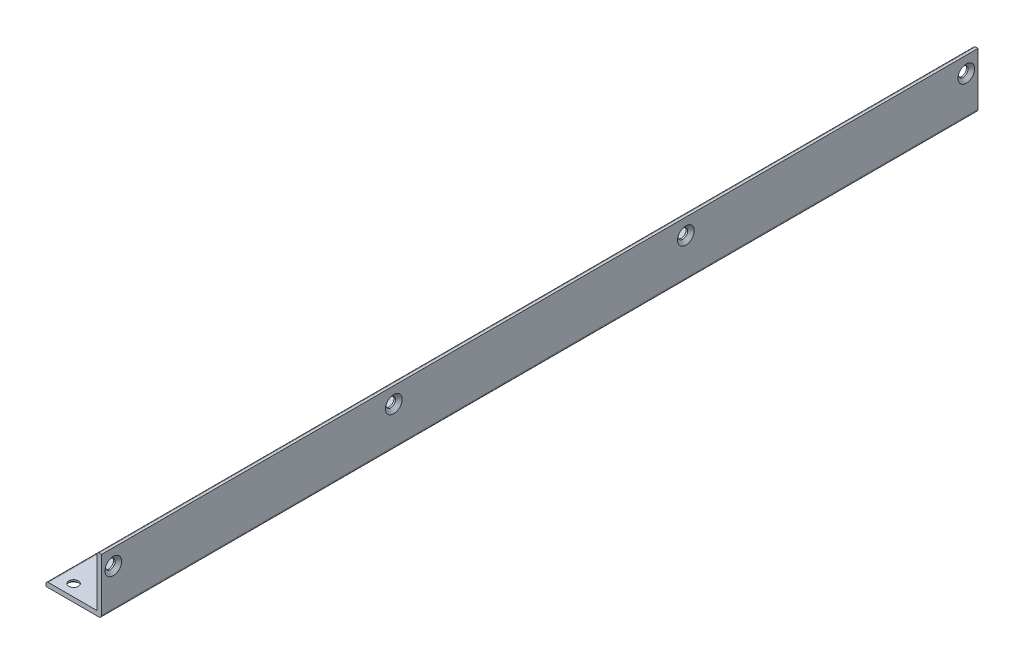
SolidWorks part; units mm, degrees
material "6061-T6 (SS)"
ref_plane "Front Plane" through (0, 0, 0) normal (0, 0, 1) x (1, 0, 0)
ref_plane "Top Plane" through (0, 0, 0) normal (0, 1, 0) x (1, 0, 0)
ref_plane "Right Plane" through (0, 0, 0) normal (1, 0, 0) x (0, 0, -1)
sketch "Sketch2" plane through (0, 0, 0) normal (0, 0, 1) x (1, 0, 0)
  line L0 (-9.525, 0) -> (9.525, 0)
  line L1 (9.525, 0) -> (9.525, 19.05)
  line L2 (9.525, 19.05) -> (7.9375, 19.05) construction
  line L3 (7.9375, 18.2563) -> (7.9375, 2.3812)
  line L4 (7.1438, 1.5875) -> (-8.7313, 1.5875)
  line L5 (-9.525, 0) -> (-9.525, 1.5875) construction
  line L6 (8.7313, 19.05) -> (9.525, 19.05)
  line L7 (-9.525, 0.7937) -> (-9.525, 0)
  arc A0 (7.9375, 18.2563) -> (8.7313, 19.05) centre (8.7313, 18.2563) cw
  arc A1 (-9.525, 0.7937) -> (-8.7313, 1.5875) centre (-8.7313, 0.7937) cw
  arc A2 (7.9375, 2.3812) -> (7.1438, 1.5875) centre (7.1438, 2.3812) cw
  dimension "Vert" = 19.05
  dimension "Horz" = 19.05
  dimension "Thickness" = 1.5875
extrude "Boss-Extrude1" add sketch "Sketch2" along normal mid plane 300
ref_plane "Contact Plane 1" through (0, 1.5875, 0) normal (0, 1, 0) x (1, 0, 0)
ref_plane "Contact Plane 2" through (7.9375, 0, 0) normal (-1, 0, 0) x (0, 0, 1)
sketch "Sketch6" plane through (0, 0, 0) normal (0, -1, 0) x (1, 0, 0)
  line L0 (9.525, 146) -> (-4.0625, 146) construction
  line L1 (9.525, 150) -> (9.525, -150) construction
  line L2 (-9.525, 150) -> (9.525, 150) construction
  line L3 (9.525, 0) -> (-9.525, 0) construction
  line L4 (-9.525, 150) -> (-9.525, -150) construction
  point P7 (-4.0625, 146)
  point P11 (-4.0625, -146)
  dimension "D1" = 4
  dimension "D2" = 13.5875
hole_wizard "CSK for #4 Flat Head Machine Screw (100)1" positions "Sketch7" profile "Sketch8" countersink size "#4" standard "ANSI Inch" end condition through all
sketch "Sketch7" plane through (0, 0, 0) normal (0, -1, 0) x (-1, 0, 0)
  point P0 (4.0625, -146)
  point P3 (4.0625, 146)
sketch "Sketch8" plane through (-4.0625, 0, 146) normal (1, 0, 0) x (0, 0, -1)
  line L0 (0, 0) -> (0, 19.05)
  line L1 (0, 19.05) -> (1.6319, 19.05)
  line L2 (1.6319, 19.05) -> (1.6319, 1.0284)
  line L3 (1.6319, 1.0284) -> (2.8575, 0)
  line L5 (2.8575, 0) -> (0, 0)
  line L6 (-1.6319, 1.0284) -> (-2.8575, 0) construction
  line L11 (0, -6.35) -> (0, 107.95) construction
  dimension "Thru Hole Dia." = 3.2639
  dimension "Thru Hole Depth" = 19.05
  dimension "Near C'Sink Dia." = 5.715
  dimension "Near C'Sink Angle" = 100
sketch "Sketch9" plane through (9.525, 0, 0) normal (1, 0, 0) x (0, 0, -1)
  line L0 (-146, 0) -> (-146, 13.5875) construction
  line L1 (0, 0) -> (0, 19.05) construction
  line L2 (-150, 0) -> (150, 0) construction
  line L3 (-150, 19.05) -> (150, 19.05) construction
  point P4 (-146, 13.5875)
  point P10 (146, 13.5875)
  dimension "D1" = 13.5875
hole_wizard "CSK for #4 Flat Head Machine Screw (100)2" positions "Sketch10" profile "Sketch11" countersink size "#4" standard "ANSI Inch" end condition through all
sketch "Sketch10" plane through (9.525, 0, 0) normal (1, 0, 0) x (0, 0, -1)
  point P0 (-146, 13.5875)
  point P3 (146, 13.5875)
sketch "Sketch11" plane through (9.525, 13.5875, 146) normal (0, 1, 0) x (0, 0, -1)
  line L0 (0, 0) -> (0, 19.05)
  line L1 (0, 19.05) -> (1.6319, 19.05)
  line L2 (1.6319, 19.05) -> (1.6319, 1.0284)
  line L3 (1.6319, 1.0284) -> (2.8575, 0)
  line L5 (2.8575, 0) -> (0, 0)
  line L6 (-1.6319, 1.0284) -> (-2.8575, 0) construction
  line L11 (0, -6.35) -> (0, 107.95) construction
  dimension "Thru Hole Dia." = 3.2639
  dimension "Thru Hole Depth" = 19.05
  dimension "Near C'Sink Dia." = 5.715
  dimension "Near C'Sink Angle" = 100
fillet "Fillet1" radius 1 1 edges at (9.525, 0, 0)
sketch "Sketch27" plane through (0, 1.5875, 0) normal (0, 1, 0) x (1, 0, 0)
  line L0 (7.1438, -150) -> (7.1438, 150) construction
  line L1 (7.1438, -150) -> (-8.7313, -150) construction
  point P0 (3.4938, -129.88)
  point P1 (-1.3062, -129.88)
  dimension "D1" = 4.8
  dimension "D2" = 3.65
  dimension "D3" = 20.12
hole_wizard "#2 Clearance Hole1" positions "Sketch28" profile "Sketch30" hole size "#2" standard "ANSI Inch" end condition through all
sketch "Sketch28" plane through (0, 1.5875, 0) normal (0, 1, 0) x (1, 0, 0)
  point P0 (3.4938, -129.88)
  point P3 (-1.3062, -129.88)
sketch "Sketch30" plane through (3.4938, 1.5875, 129.88) normal (1, 0, 0) x (0, 0, 1)
  line L0 (0, 0) -> (0, 1.5875)
  line L1 (0, 1.5875) -> (2.0574, 1.5875)
  line L2 (1.2192, 0.6233) -> (1.2192, 0)
  line L5 (1.2192, 0) -> (0, 0)
  line L7 (2.0574, 1.5875) -> (1.2192, 0.6233)
  line L8 (-2.0574, 1.5875) -> (-1.2192, 0.6233) construction
  line L11 (0, -6.35) -> (0, 107.95) construction
  dimension "Thru Hole Dia." = 2.4384
  dimension "Thru Hole Depth" = 1.5875
  dimension "Far C'Sink Dia." = 4.1148
  dimension "Far C'Sink Angle" = 82
sketch "Sketch32" plane through (0, 0, 0) normal (0, -1, 0) x (1, 0, 0)
  line L0 (-4.0625, -150) -> (-4.0625, -50) construction
  line L1 (-9.525, -150) -> (8.525, -150) construction
  point P0 (-4.0625, -146)
  point P7 (-4.0625, -50)
  dimension "D1" = 100
hole_wizard "CSK for #4 Flat Head Machine Screw (100)3" positions "Sketch33" profile "Sketch34" countersink size "#4" standard "ANSI Inch" end condition through all
sketch "Sketch33" plane through (0, 0, 0) normal (0, -1, 0) x (-1, 0, 0)
  point P0 (4.0625, 50)
sketch "Sketch34" plane through (-4.0625, 0, -50) normal (1, 0, 0) x (0, 0, -1)
  line L0 (0, 0) -> (0, 19.05)
  line L1 (0, 19.05) -> (1.6319, 19.05)
  line L2 (1.6319, 19.05) -> (1.6319, 1.0284)
  line L3 (1.6319, 1.0284) -> (2.8575, 0)
  line L5 (2.8575, 0) -> (0, 0)
  line L6 (-1.6319, 1.0284) -> (-2.8575, 0) construction
  line L11 (0, -6.35) -> (0, 107.95) construction
  dimension "Thru Hole Dia." = 3.2639
  dimension "Thru Hole Depth" = 19.05
  dimension "Near C'Sink Dia." = 5.715
  dimension "Near C'Sink Angle" = 100
sketch "Sketch35" plane through (9.525, 0, 0) normal (1, 0, 0) x (0, 0, -1)
  line L0 (150, 13.5875) -> (50, 13.5875) construction
  line L1 (150, 1) -> (150, 19.05) construction
  point P0 (146, 13.5875)
  point P7 (50, 13.5875)
  dimension "D1" = 100
hole_wizard "CSK for #4 Flat Head Machine Screw (100)4" positions "Sketch36" profile "Sketch37" countersink size "#4" standard "ANSI Inch" end condition through all
sketch "Sketch36" plane through (9.525, 0, 0) normal (1, 0, 0) x (0, 0, -1)
  point P0 (50, 13.5875)
sketch "Sketch37" plane through (9.525, 13.5875, -50) normal (0, 1, 0) x (0, 0, -1)
  line L0 (0, 0) -> (0, 19.05)
  line L1 (0, 19.05) -> (1.6319, 19.05)
  line L2 (1.6319, 19.05) -> (1.6319, 1.0284)
  line L3 (1.6319, 1.0284) -> (2.8575, 0)
  line L5 (2.8575, 0) -> (0, 0)
  line L6 (-1.6319, 1.0284) -> (-2.8575, 0) construction
  line L11 (0, -6.35) -> (0, 107.95) construction
  dimension "Thru Hole Dia." = 3.2639
  dimension "Thru Hole Depth" = 19.05
  dimension "Near C'Sink Dia." = 5.715
  dimension "Near C'Sink Angle" = 100
sketch "Sketch38" plane through (9.525, 0, 0) normal (1, 0, 0) x (0, 0, -1)
  line L0 (50, 13.5875) -> (-50, 13.5875) construction
  point P6 (-50, 13.5875)
  dimension "D1" = 100
hole_wizard "CSK for #4 Flat Head Machine Screw (100)5" positions "Sketch39" profile "Sketch40" countersink size "#4" standard "ANSI Inch" end condition through all
sketch "Sketch39" plane through (9.525, 0, 0) normal (1, 0, 0) x (0, 0, -1)
  point P0 (-50, 13.5875)
sketch "Sketch40" plane through (9.525, 13.5875, 50) normal (0, 1, 0) x (0, 0, -1)
  line L0 (0, 0) -> (0, 19.05)
  line L1 (0, 19.05) -> (1.6319, 19.05)
  line L2 (1.6319, 19.05) -> (1.6319, 1.0284)
  line L3 (1.6319, 1.0284) -> (2.8575, 0)
  line L5 (2.8575, 0) -> (0, 0)
  line L6 (-1.6319, 1.0284) -> (-2.8575, 0) construction
  line L11 (0, -6.35) -> (0, 107.95) construction
  dimension "Thru Hole Dia." = 3.2639
  dimension "Thru Hole Depth" = 19.05
  dimension "Near C'Sink Dia." = 5.715
  dimension "Near C'Sink Angle" = 100
sketch "Sketch41" plane through (0, 0, 0) normal (0, -1, 0) x (1, 0, 0)
  line L0 (-4.0625, -50) -> (-4.0625, 50) construction
  point P4 (-4.0625, 50)
  point P5 (-4.0625, 50)
  dimension "D1" = 100
hole_wizard "CSK for #4 Flat Head Machine Screw (100)6" positions "Sketch42" profile "Sketch43" countersink size "#4" standard "ANSI Inch" end condition through all
sketch "Sketch42" plane through (0, 0, 0) normal (0, -1, 0) x (-1, 0, 0)
  point P0 (4.0625, -50)
sketch "Sketch43" plane through (-4.0625, 0, 50) normal (1, 0, 0) x (0, 0, -1)
  line L0 (0, 0) -> (0, 19.05)
  line L1 (0, 19.05) -> (1.6319, 19.05)
  line L2 (1.6319, 19.05) -> (1.6319, 1.0284)
  line L3 (1.6319, 1.0284) -> (2.8575, 0)
  line L5 (2.8575, 0) -> (0, 0)
  line L6 (-1.6319, 1.0284) -> (-2.8575, 0) construction
  line L11 (0, -6.35) -> (0, 107.95) construction
  dimension "Thru Hole Dia." = 3.2639
  dimension "Thru Hole Depth" = 19.05
  dimension "Near C'Sink Dia." = 5.715
  dimension "Near C'Sink Angle" = 100
sketch "Sketch44" plane through (0, 0, 150) normal (0, 0, 1) x (1, 0, 0)
  line L0 (7.9375, 6.5875) -> (7.9375, 1.5875)
  line L1 (7.9375, 18.2563) -> (7.9375, 2.3812) construction
  line L2 (2.9375, 1.5875) -> (7.9375, 6.5875)
  line L3 (7.1438, 1.5875) -> (-8.7313, 1.5875) construction
  line L4 (2.9375, 1.5875) -> (7.9375, 1.5875)
  dimension "D1" = 5
  dimension "D2" = 5
extrude "Cut-Extrude1" cut sketch "Sketch44" against normal blind 25
ref_plane "Plane1" through (0, 0, 0) normal (0, 0, 1) x (1, 0, 0)
mirror "Mirror1" about plane through (0, 0, 0) normal (0, 0, 1) of "Cut-Extrude1"
